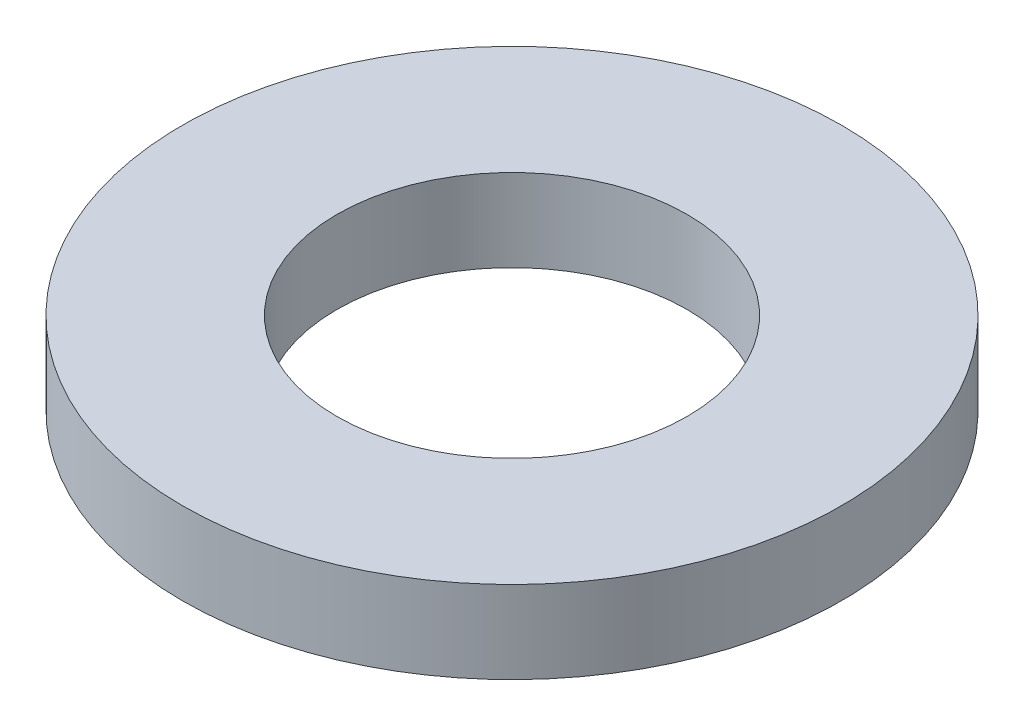
SolidWorks part; units mm, degrees
ref_plane "Front Plane" through (0, 0, 0) normal (0, 0, 1) x (1, 0, 0)
ref_plane "Top Plane" through (0, 0, 0) normal (0, 1, 0) x (1, 0, 0)
ref_plane "Right Plane" through (0, 0, 0) normal (1, 0, 0) x (0, 0, -1)
sketch "Sketch1" plane through (0, 0, 0) normal (0, 1, 0) x (1, 0, 0)
  circle A0 centre (0, 0) radius 8
  circle A1 centre (0, 0) radius 4.25
  dimension "D1" = 16
  dimension "D2" = 8.5
extrude "Boss-Extrude1" add sketch "Sketch1" along normal blind 2
